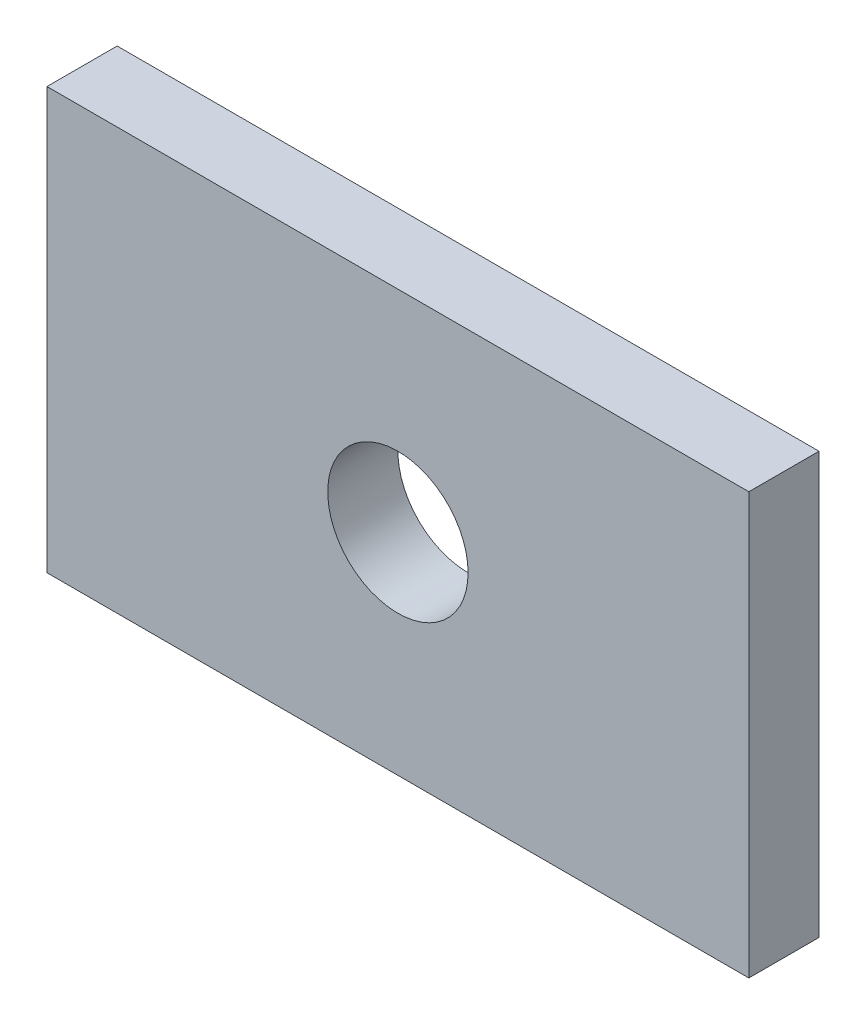
SolidWorks part; units mm, degrees
ref_plane "Front Plane" through (0, 0, 0) normal (0, 0, 1) x (1, 0, 0)
ref_plane "Top Plane" through (0, 0, 0) normal (0, 1, 0) x (1, 0, 0)
ref_plane "Right Plane" through (0, 0, 0) normal (1, 0, 0) x (0, 0, -1)
sketch "Sketch1" plane through (0, 0, 0) normal (0, 0, 1) x (1, 0, 0)
  line L1 (50, 30) -> (-50, 30)
  line L2 (50, 30) -> (50, -30)
  line L3 (50, -30) -> (-50, -30)
  line L4 (-50, 30) -> (-50, -30)
  line L5 (50, 30) -> (-50, -30) construction
  line L6 (50, -30) -> (-50, 30) construction
  circle A0 centre (0, 0) radius 10
  point P0 (0, 0)
  dimension "D3" = 20
  dimension "D1" = 100
  dimension "D2" = 60
extrude "Boss-Extrude1" add sketch "Sketch1" along normal blind 10
equation "\"Hole_D\"=20"
